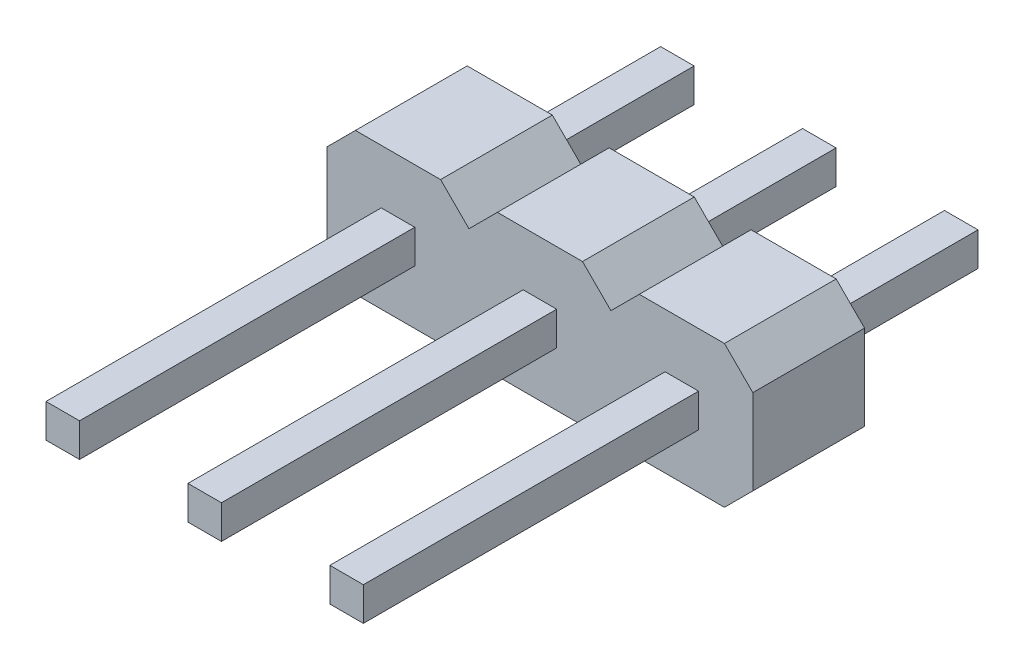
SolidWorks part; units mm, degrees
ref_plane "前视基准面" through (0, 0, 0) normal (0, 0, 1) x (1, 0, 0)
ref_plane "上视基准面" through (0, 0, 0) normal (0, 1, 0) x (1, 0, 0)
ref_plane "右视基准面" through (0, 0, 0) normal (1, 0, 0) x (0, 0, -1)
sketch "草图1" plane through (0, 0, 0) normal (0, 0, 1) x (1, 0, 0)
  line L0 (-0.762, 1.27) -> (-1.27, 0.762)
  line L1 (-0.762, 1.27) -> (0.762, 1.27)
  line L2 (-1.27, 0.762) -> (-1.27, -0.762)
  line L3 (-0.762, -1.27) -> (0.762, -1.27)
  line L5 (-1.27, 1.27) -> (1.27, -1.27) construction
  line L6 (-1.27, -1.27) -> (1.27, 1.27) construction
  line L7 (0.762, 1.27) -> (1.27, 0.762)
  line L8 (1.27, -0.762) -> (0.762, -1.27)
  line L9 (-1.27, -0.762) -> (-0.762, -1.27)
  line L10 (2.84, 0.3) -> (2.84, -0.3)
  line L11 (-0.3, 0.3) -> (0.3, 0.3)
  line L12 (-0.3, 0.3) -> (-0.3, -0.3)
  line L13 (-0.3, -0.3) -> (0.3, -0.3)
  line L14 (0.3, 0.3) -> (0.3, -0.3)
  line L15 (-0.4097, 0.4097) -> (0.4097, -0.4097) construction
  line L16 (-0.4097, -0.4097) -> (0.4097, 0.4097) construction
  line L17 (-0.3, 0.3) -> (0.3, -0.3) construction
  line L18 (-0.3, -0.3) -> (0.3, 0.3) construction
  line L19 (2.24, -0.3) -> (2.84, -0.3)
  line L20 (2.24, 0.3) -> (2.24, -0.3)
  line L21 (2.24, 0.3) -> (2.84, 0.3)
  line L22 (1.778, 1.27) -> (3.302, 1.27)
  line L23 (3.302, 1.27) -> (3.81, 0.762)
  line L25 (3.81, -0.762) -> (3.302, -1.27)
  line L26 (1.778, -1.27) -> (3.302, -1.27)
  line L27 (1.27, -0.762) -> (1.778, -1.27)
  line L29 (1.778, 1.27) -> (1.27, 0.762)
  line L30 (5.38, 0.3) -> (5.38, -0.3)
  line L31 (4.78, -0.3) -> (5.38, -0.3)
  line L32 (4.78, 0.3) -> (4.78, -0.3)
  line L33 (4.78, 0.3) -> (5.38, 0.3)
  line L34 (4.318, 1.27) -> (5.842, 1.27)
  line L35 (5.842, 1.27) -> (6.35, 0.762)
  line L36 (6.35, 0.762) -> (6.35, -0.762)
  line L37 (6.35, -0.762) -> (5.842, -1.27)
  line L38 (4.318, -1.27) -> (5.842, -1.27)
  line L39 (3.81, -0.762) -> (4.318, -1.27)
  line L41 (4.318, 1.27) -> (3.81, 0.762)
  line L42 (1.27, 0.762) -> (1.27, -0.762) [skipped]
  line L43 (3.81, 0.762) -> (3.81, -0.762) [skipped]
  point P0 (0, 0)
  point P14 (0, 0)
  point P19 (0, 0)
  dimension "D1" = 2.54
  dimension "D2" = 2.54
  dimension "D3" = 0.6
  dimension "D4" = 0.6
  dimension "D5" = 3
extrude "凸台-拉伸1" add sketch "草图1" along normal blind 2
sketch "草图2" plane through (0, 0, 2) normal (0, 0, 1) x (1, 0, 0)
  line L1 (-0.3, 0.3) -> (0.3, 0.3)
  line L2 (-0.3, 0.3) -> (-0.3, -0.3)
  line L3 (-0.3, -0.3) -> (0.3, -0.3)
  line L4 (0.3, 0.3) -> (0.3, -0.3)
  line L5 (2.24, 0.3) -> (2.84, 0.3)
  line L6 (2.24, 0.3) -> (2.24, -0.3)
  line L7 (2.24, -0.3) -> (2.84, -0.3)
  line L8 (2.84, 0.3) -> (2.84, -0.3)
  line L9 (4.78, 0.3) -> (5.38, 0.3)
  line L10 (4.78, 0.3) -> (4.78, -0.3)
  line L11 (4.78, -0.3) -> (5.38, -0.3)
  line L12 (5.38, 0.3) -> (5.38, -0.3)
extrude "凸台-拉伸2" add sketch "草图2" along normal blind 6 and the other way blind 5
